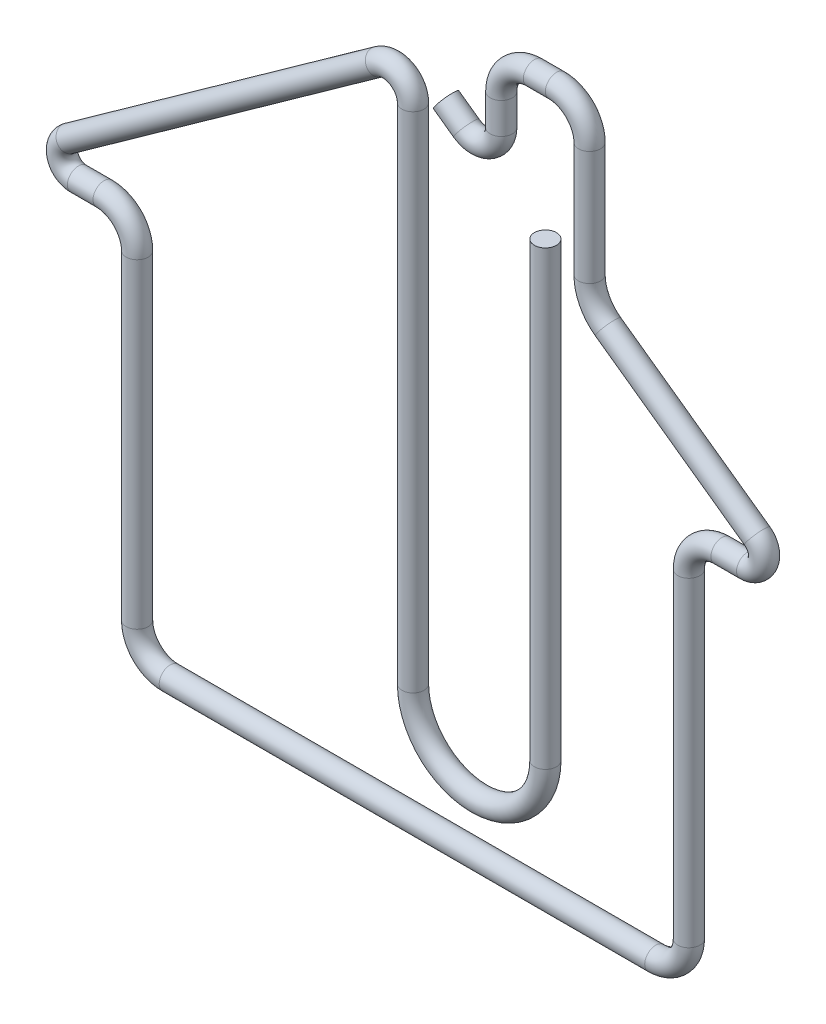
SolidWorks part; units mm, degrees
ref_plane "Спереди" through (0, 0, 0) normal (0, 0, 1) x (1, 0, 0)
ref_plane "Сверху" through (0, 0, 0) normal (0, 1, 0) x (1, 0, 0)
ref_plane "Справа" through (0, 0, 0) normal (1, 0, 0) x (0, 0, -1)
sketch "Эскиз1" plane through (0, 0, 0) normal (0, 0, 1) x (1, 0, 0)
  line L0 (0, 42.5) -> (-35, 17.5) construction
  line L1 (-25, -17.5) -> (25, -17.5) construction
  line L2 (-25, -17.5) -> (-25, 17.5) construction
  line L3 (-25, 17.5) -> (25, 17.5) construction
  line L4 (25, -17.5) -> (25, 17.5) construction
  line L5 (-25, -17.5) -> (25, 17.5) construction
  line L6 (-25, 17.5) -> (25, -17.5) construction
  line L7 (-35, 17.5) -> (-25, 17.5) construction
  line L8 (0, 42.5) -> (35, 17.5) construction
  line L9 (35, 17.5) -> (25, 17.5) construction
  line L10 (6, 63) -> (6, -7) construction
  line L11 (12, 63) -> (12, -7) construction
  line L12 (0, 63) -> (0, -7) construction
  line L13 (8, 36.7857) -> (8, 46.5) construction
  line L14 (8, 46.5) -> (16, 46.5) construction
  line L15 (16, 46.5) -> (16, 31.0714) construction
  arc A0 (12, 63) -> (0, 63) centre (6, 63) ccw construction
  arc A1 (0, -7) -> (12, -7) centre (6, -7) ccw construction
  point P0 (0, 0)
  point P11 (6, 28)
  dimension "D1" = 50
  dimension "D2" = 35
  dimension "D3" = 25
  dimension "D4" = 10
  dimension "D5" = 12
  dimension "D6" = 70
  dimension "D7" = 28
  dimension "D8" = 4
  dimension "D9" = 4
  dimension "D10" = 4
sketch "Эскиз2" plane through (0, 0, 0) normal (0, 0, 1) x (1, 0, 0)
  line L0 (-25, 14.5) -> (-25, -14.5)
  line L1 (-22, -17.5) -> (22, -17.5)
  line L2 (25, -14.5) -> (25, 14.5)
  line L3 (28, 17.5) -> (30.3193, 17.5)
  line L4 (31.1912, 20.2206) -> (17.675, 29.875)
  line L5 (16, 33.1299) -> (16, 43.5)
  line L6 (13, 46.5) -> (11, 46.5)
  line L7 (8, 43.5) -> (8, 40.6721)
  line L8 (4.8375, 39.0446) -> (3, 40.3571)
  line L9 (0, 42.5) -> (35, 17.5) construction
  line L10 (-28, 17.5) -> (-30.3193, 17.5)
  line L11 (-31.1912, 20.2206) -> (-3.1625, 40.2411)
  line L12 (0, 38.6136) -> (0, -7)
  line L13 (12, -7) -> (12, 33.9286)
  line L14 (12, 63) -> (12, -7) construction
  arc A0 (0, -7) -> (12, -7) centre (6, -7) ccw
  arc A1 (-3.1625, 40.2411) -> (0, 38.6136) centre (-2, 38.6136) cw
  arc A2 (16, 43.5) -> (13, 46.5) centre (13, 43.5) ccw
  arc A3 (11, 46.5) -> (8, 43.5) centre (11, 43.5) ccw
  arc A4 (8, 40.6721) -> (4.8375, 39.0446) centre (6, 40.6721) cw
  arc A5 (17.675, 29.875) -> (16, 33.1299) centre (20, 33.1299) cw
  arc A6 (31.1912, 20.2206) -> (30.3193, 17.5) centre (30.3193, 19) cw
  arc A7 (-30.3193, 17.5) -> (-31.1912, 20.2206) centre (-30.3193, 19) cw
  arc A8 (28, 17.5) -> (25, 14.5) centre (28, 14.5) ccw
  arc A9 (25, -14.5) -> (22, -17.5) centre (22, -14.5) cw
  arc A10 (-22, -17.5) -> (-25, -14.5) centre (-22, -14.5) cw
  arc A11 (-28, 17.5) -> (-25, 14.5) centre (-28, 14.5) cw
  point P35 (0, 42.5)
  point P38 (16, 46.5)
  point P41 (8, 46.5)
  point P44 (8, 36.7857)
  point P47 (16, 31.0714)
  point P50 (35, 17.5)
  point P53 (-35, 17.5)
  point P56 (25, 17.5)
  point P59 (25, -17.5)
  point P62 (-25, -17.5)
  point P65 (-25, 17.5)
  dimension "D2" = 2
  dimension "D3" = 3
  dimension "D4" = 2
  dimension "D5" = 4
  dimension "D6" = 1.5
  dimension "D7" = 3
  dimension "D1" = 3
ref_plane "Плоскость1" through (12, 33.9286, 0) normal (0, -1, 0) x (-1, 0, 0)
sketch "Эскиз3" plane through (12, 33.9286, 0) normal (0, -1, 0) x (-1, 0, 0)
  circle A0 centre (0, 0) radius 1
  dimension "D1" = 2
sweep "По траектории2" add profiles "Эскиз3" path "Эскиз2"
